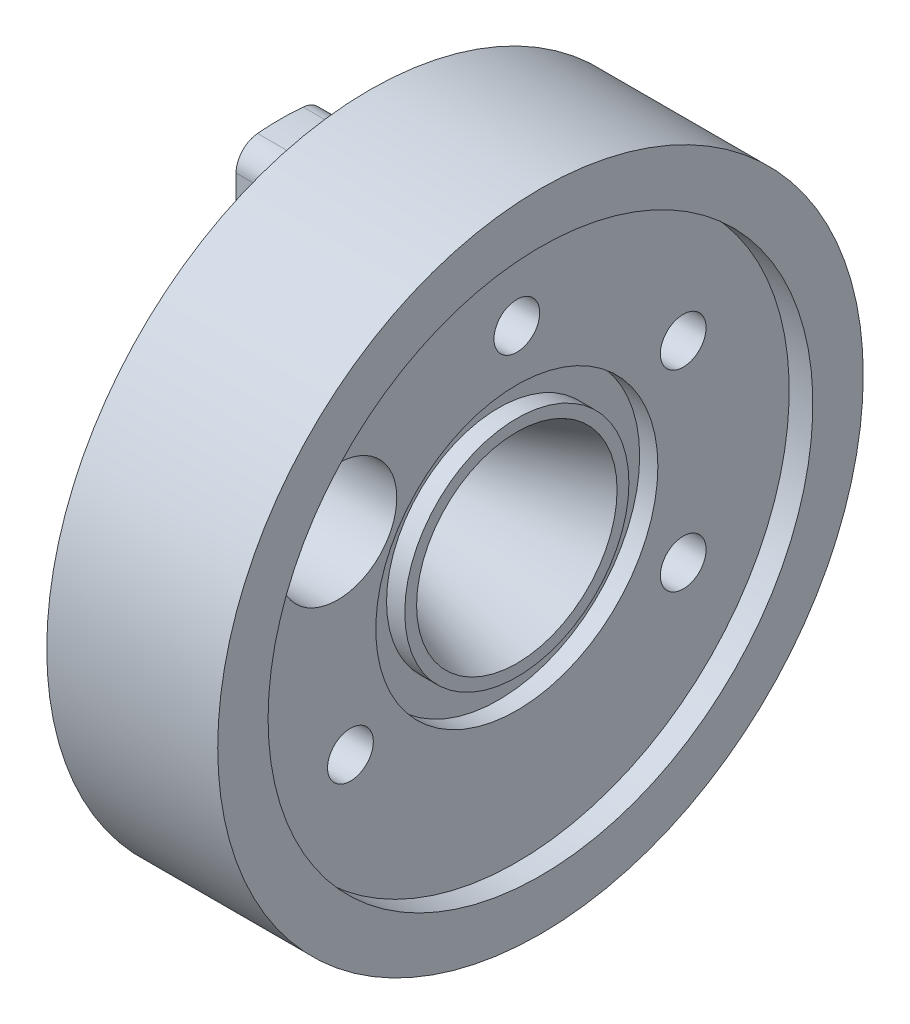
SolidWorks part; units mm, degrees
material "6061-T6 (SS)"
ref_plane "Front Plane" through (0, 0, 0) normal (0, 0, 1) x (1, 0, 0)
ref_plane "Top Plane" through (0, 0, 0) normal (0, 1, 0) x (1, 0, 0)
ref_plane "Right Plane" through (0, 0, 0) normal (1, 0, 0) x (0, 0, -1)
ref_axis "Axis1" through (-88.99, 0, 0) along (1, 0, 0)
sketch "Sketch1" plane through (0, 0, 0) normal (0, 0, 1) x (1, 0, 0)
  line L1 (9.5758, 34.671) -> (27.94, 34.671)
  line L2 (27.94, 34.671) -> (27.94, 29.2608)
  line L3 (27.94, 29.2608) -> (25.4, 29.2608)
  line L4 (0, 0) -> (25.4, 0)
  line L5 (9.5758, 34.671) -> (9.5758, 27.94)
  line L6 (9.5758, 27.94) -> (0, 27.94)
  line L15 (0, 27.94) -> (0, 0)
  line L20 (25.4, 29.2608) -> (25.4, 0)
  dimension "D2" = 27.94
  dimension "D3" = 2.54
  dimension "D4" = 9.5758
  dimension "D5" = 29.2608
  dimension "D6" = 34.671
  dimension "D10" = 25.4
revolve "Revolve2" add sketch "Sketch1" angle 360 about axis through (-88.99, 0, 0) along (1, 0, 0)
hole_wizard "NPT Center Bore" positions "Sketch27" profile "Sketch28" size "1/4" standard "ANSI Inch" end condition through all
sketch "Sketch27" plane through (0, 0, 0) normal (-1, 0, 0) x (0, 0, 1)
  point P0 (0, 0)
sketch "Sketch28" plane through (0, 0, 0) normal (0, 1, 0) x (0, 0, 1)
  line L0 (0, 0) -> (0, 27.94)
  line L1 (0, 27.94) -> (5.5626, 27.94)
  line L2 (-6.558, 10.16) -> (-6.8622, 0) construction
  line L3 (5.5626, 27.94) -> (5.5626, 10.16)
  line L4 (5.5626, 10.16) -> (6.558, 10.16)
  line L5 (6.558, 10.16) -> (6.8622, 0)
  line L7 (6.8622, 0) -> (0, 0)
  line L8 (0, -6.35) -> (0, 107.95) construction
  line L11 (-5.5626, 10.16) -> (-6.558, 10.16) construction
  dimension "Thru Tap Drill Dia." = 11.1252
  dimension "Thru Tap Drill Depth" = 27.94
  dimension "Thread Dia." = 13.7244
  dimension "Thread Angle" = 3.43
  dimension "Thread Depth" = 10.16
hole_wizard "Mounting Hole" positions "Sketch9" profile "Sketch10" hole size "#10" standard "ANSI Inch" end condition through all
sketch "Sketch9" plane through (0, 0, 0) normal (-1, 0, 0) x (0, 0, 1)
  line L3 (0, 0) -> (0, 20.6375)
  point P12 (0, 20.6375)
  dimension "D1" = 20.6375
sketch "Sketch10" plane through (0, 20.6375, 0) normal (0, 1, 0) x (0, 0, 1)
  line L0 (0, 0) -> (0, 27.94)
  line L1 (0, 27.94) -> (2.4574, 27.94)
  line L2 (2.4574, 27.94) -> (2.4574, 0)
  line L5 (2.4574, 0) -> (0, 0)
  line L11 (0, -6.35) -> (0, 107.95) construction
  dimension "Thru Hole Dia." = 4.9149
  dimension "Thru Hole Depth" = 27.94
pattern_circular "CirPattern1" count 3 over 360 about axis through (0, 0, 0) along (1, 0, 0) of "Mounting Hole"
sketch "Sketch26" plane through (25.4, 0, 0) normal (1, 0, 0) x (0, 0, -1)
  circle A0 centre (0, 0) radius 15.1511
  circle A1 centre (0, 0) radius 12.0396
  dimension "D1" = 30.3022
  dimension "D2" = 3.1115
extrude "Axial O-Ring Gland" cut sketch "Sketch26" against normal blind 1.9558
sketch "Sketch45" plane through (0, 0, 0) normal (0, 0, 1) x (1, 0, 0)
  line L0 (27.94, 34.671) -> (9.5758, 34.671) construction
  line L1 (17.4879, 33.655) -> (20.0279, 33.655) construction
  line L2 (23.6347, 34.671) -> (20.0279, 34.671)
  line L3 (23.6347, 34.671) -> (23.6347, 32.639)
  line L4 (23.6347, 32.639) -> (20.0279, 32.639)
  line L5 (20.0279, 34.671) -> (20.0279, 32.639)
  line L6 (17.4879, 34.671) -> (13.8811, 34.671)
  line L7 (17.4879, 34.671) -> (17.4879, 32.639)
  line L8 (17.4879, 32.639) -> (13.8811, 32.639)
  line L9 (13.8811, 34.671) -> (13.8811, 32.639)
  line L10 (27.94, 34.671) -> (9.5758, 34.671) construction
  line L11 (0, 0) -> (50000, 0) construction
  point P12 (18.7579, 34.671)
  point P13 (18.7579, 33.655)
  dimension "D1" = 3.6068
  dimension "D2" = 2.54
  dimension "D3" = 2.032
revolve "Radial O-Ring Gland 2-144" [suppressed] cut sketch "Sketch45" angle 360 about L11
sketch "Sketch30" plane through (0, 0, 0) normal (0, 0, 1) x (1, 0, 0)
  line L3 (25.4, -5.5626) -> (25.4, 5.5626) construction
  line L5 (25.4, -12.0396) -> (25.4, 12.0396) construction
  line L6 (25.4, -5.5626) -> (25.4, 5.5626) construction
  line L7 (11.0939, 5.5626) -> (25.4, 10.7696)
  line L8 (25.4, -12.0396) -> (25.4, 12.0396) construction
  line L9 (25.4, 10.7696) -> (25.4, 5.5626)
  line L10 (25.4, 5.5626) -> (11.0939, 5.5626)
  dimension "D1" = 20
  dimension "D2" = 1.27
revolve "Flow Cone" cut sketch "Sketch30" angle 360 about axis through (-88.99, 0, 0) along (1, 0, 0)
hole_wizard "Pressure Tap Clearance Hole" positions "Sketch40" profile "Sketch41" hole size "1/2" standard "ANSI Inch" end condition through all
sketch "Sketch40" plane through (0, 0, 0) normal (-1, 0, 0) x (0, 0, 1)
  line L0 (0, 0) -> (0, 20.6375)
  line L2 (0, 0) -> (19.2474, 11.1125)
  point P0 (19.2474, 11.1125)
  dimension "D1" = 60
sketch "Sketch41" plane through (0, 11.1125, 19.2474) normal (0, 1, 0) x (0, 0, 1)
  line L0 (0, 0) -> (0, 27.94)
  line L1 (0, 27.94) -> (6.35, 27.94)
  line L2 (6.35, 27.94) -> (6.35, 0)
  line L5 (6.35, 0) -> (0, 0)
  line L11 (0, -6.35) -> (0, 107.95) construction
  dimension "Thru Hole Dia." = 12.7
  dimension "Thru Hole Depth" = 27.94
hole_wizard "Thermocouple Clearance Hole" positions "Sketch43" profile "Sketch44" hole size "#10" standard "ANSI Inch" end condition through all
sketch "Sketch43" plane through (0, 0, 0) normal (-1, 0, 0) x (0, 0, 1)
  line L0 (-17.8726, 10.3188) -> (0, 0)
  line L1 (0, 0) -> (0, 20.6375)
  point P0 (-17.8726, 10.3188)
  dimension "D1" = 60
sketch "Sketch44" plane through (0, 10.3188, -17.8726) normal (0, 1, 0) x (0, 0, 1)
  line L0 (0, 0) -> (0, 27.94)
  line L1 (0, 27.94) -> (2.4574, 27.94)
  line L2 (2.4574, 27.94) -> (2.4574, 0)
  line L5 (2.4574, 0) -> (0, 0)
  line L11 (0, -6.35) -> (0, 107.95) construction
  dimension "Thru Hole Dia." = 4.9149
  dimension "Thru Hole Depth" = 27.94
sketch "Sketch7" plane through (0, 0, 0) normal (-1, 0, 0) x (0, 0, 1)
  line L0 (15.4962, -3.4474) -> (25.5539, -9.2543)
  line L1 (0, 0) -> (0, 34.7345) construction
  line L2 (-4.7625, 15.1438) -> (-4.7625, 26.7575)
  line L3 (4.7625, 15.1438) -> (4.7625, 26.7575)
  line L4 (10.7337, -11.6963) -> (20.7914, -17.5032)
  line L5 (-10.7337, -11.6963) -> (-20.7914, -17.5032)
  line L6 (-15.4962, -3.4474) -> (-25.5539, -9.2543)
  circle A0 centre (0, 0) radius 34.7345
  arc A1 (4.7625, 26.7575) -> (-4.7625, 26.7575) centre (0, 0) ccw
  arc A2 (-4.7625, 15.1438) -> (-15.4962, -3.4474) centre (0, 0) ccw
  arc A3 (20.7914, -17.5032) -> (25.5539, -9.2543) centre (0, 0) ccw
  arc A4 (-25.5539, -9.2543) -> (-20.7914, -17.5032) centre (0, 0) ccw
  arc A5 (-10.7337, -11.6963) -> (10.7337, -11.6963) centre (0, 0) ccw
  arc A6 (15.4962, -3.4474) -> (4.7625, 15.1438) centre (0, 0) ccw
  circle A7 centre (0, 0) radius 15.875 construction
  circle A8 centre (0, 0) radius 27.178 construction
  circle A9 centre (0, 0) radius 27.7876 construction
  point P18 (0, 0)
  dimension "D2" = 31.75
  dimension "D3" = 54.356
  dimension "D4" = 55.5752
  dimension "D5" = 9.525
  dimension "D1" = 3
extrude "Cut-Extrude1" cut sketch "Sketch7" against normal up to surface (9.5758 mm away) up to face at (9.5758, 0.1587, 0.275)
fillet "Fillet1" radius 2.54 6 edges at (4.7879, -9.2543, 25.5539) (4.7879, -17.5032, 20.7914) (4.7879, -17.5032, -20.7914) (4.7879, -9.2543, -25.5539) (4.7879, 26.7575, -4.7625) (4.7879, 26.7575, 4.7625)
fillet "Fillet2" radius 6.604 6 edges at (4.7879, -11.6963, 10.7337) (4.7879, -11.6963, -10.7337) (4.7879, -3.4474, -15.4962) (4.7879, 15.1438, -4.7625) (4.7879, -3.4474, 15.4962) (4.7879, 15.1438, 4.7625)
